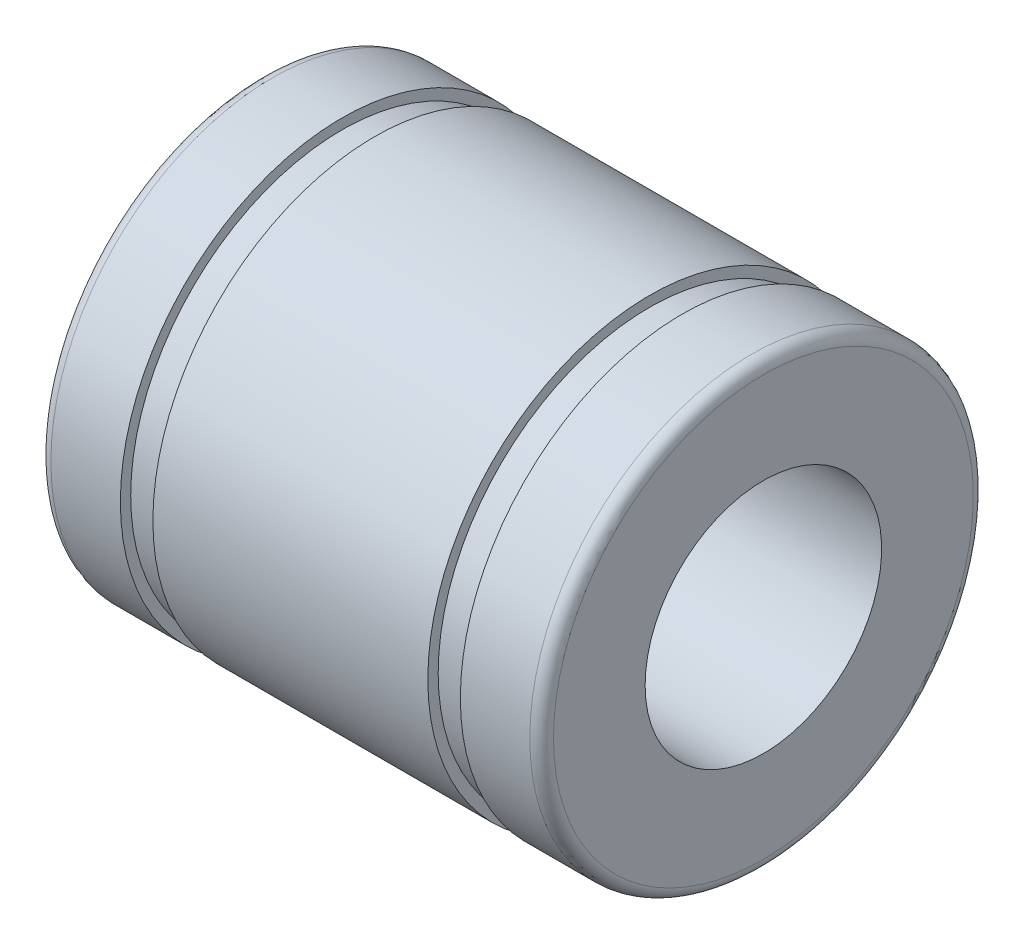
SolidWorks part; units mm, degrees
ref_plane "前视基准面" through (0, 0, 0) normal (0, 0, 1) x (1, 0, 0)
ref_plane "上视基准面" through (0, 0, 0) normal (0, 1, 0) x (1, 0, 0)
ref_plane "右视基准面" through (0, 0, 0) normal (1, 0, 0) x (0, 0, -1)
sketch "草图1" plane through (0, 0, 0) normal (0, 0, 1) x (1, 0, 0)
  line L0 (0, 0) -> (50000, 0) construction
  line L1 (0, 0) -> (0, 50000) construction
  line L3 (-8.5, 7.5) -> (8.5, 7.5)
  line L4 (-8.5, 7.5) -> (-8.5, 4)
  line L5 (-8.5, 4) -> (8.5, 4)
  line L6 (8.5, 7.5) -> (8.5, 4)
  dimension "D1" = 17
  dimension "D2" = 15
  dimension "D3" = 8
revolve "旋转1" add sketch "草图1" angle 360 about L0
sketch "草图2" plane through (0, 0, 0) normal (0, 0, 1) x (1, 0, 0)
  line L0 (0, 0) -> (50000, 0) construction
  line L1 (0, 0) -> (0, 50000) construction
  line L2 (8.5, 7.5) -> (-8.5, 7.5) construction
  line L3 (-5.75, 7.5) -> (-4.65, 7.5)
  line L4 (-5.75, 7.5) -> (-5.75, 7.15)
  line L5 (-5.75, 7.15) -> (-4.65, 7.15)
  line L6 (-4.65, 7.5) -> (-4.65, 7.15)
  line L7 (4.65, 7.5) -> (4.65, 7.15)
  line L8 (5.75, 7.15) -> (4.65, 7.15)
  line L9 (5.75, 7.5) -> (5.75, 7.15)
  line L10 (5.75, 7.5) -> (4.65, 7.5)
  dimension "D1" = 11.5
  dimension "D2" = 1.1
  dimension "D3" = 14.3
revolve "切除-旋转1" cut sketch "草图2" angle 360 about L0
fillet "圆角1" radius 0.4 2 edges at (8.5, 0, 7.5) (-8.5, 0, 7.5)
